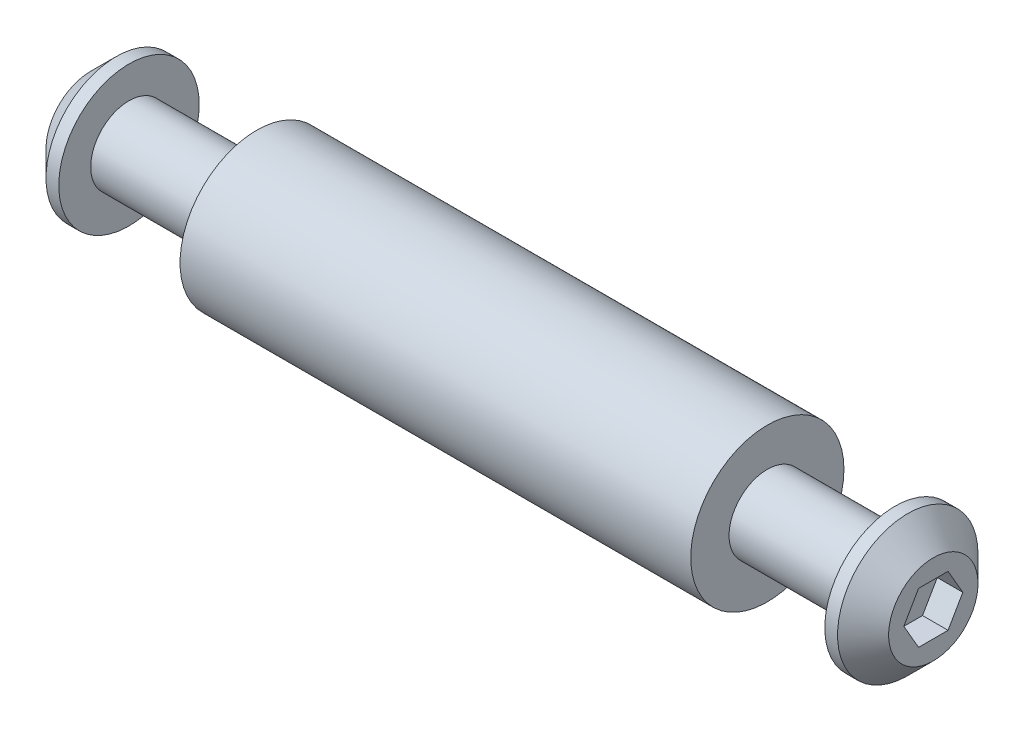
SolidWorks part; units mm, degrees
ref_plane "Front" through (0, 0, 0) normal (0, 0, 1) x (1, 0, 0)
ref_plane "Top" through (0, 0, 0) normal (0, 1, 0) x (1, 0, 0)
ref_plane "Right" through (0, 0, 0) normal (1, 0, 0) x (0, 0, -1)
sketch "Esquisse1" plane through (0, 0, 0) normal (0, 0, 1) x (1, 0, 0)
  line L0 (0, 0) -> (-18.7013, 0) construction
  line L1 (0, 0) -> (0, 7.2882) construction
  line L2 (10, 3) -> (-10, 3)
  line L3 (-10, 3) -> (-10, 1.5)
  line L4 (-10, 1.5) -> (-15, 1.5)
  line L5 (-15, 1.5) -> (-15, 2.75)
  line L6 (-15, 2.75) -> (-15.5, 2.75)
  line L7 (-15.5, 2.75) -> (-16.5, 1.75)
  line L8 (-16.5, 1.75) -> (-16.5, 0)
  line L9 (-16.5, 0) -> (16.5, 0)
  line L10 (10, 3) -> (10, 1.5)
  line L11 (10, 1.5) -> (15, 1.5)
  line L12 (15, 1.5) -> (15, 2.75)
  line L13 (15, 2.75) -> (15.5, 2.75)
  line L14 (15.5, 2.75) -> (16.5, 1.75)
  line L15 (16.5, 1.75) -> (16.5, 0)
  point P7 (-15.25, 2.75)
  point P13 (-15, 2.125)
  point P16 (0, 3)
  point P17 (15, 2.125)
  point P19 (15.25, 2.75)
  point P23 (-10.9122, 0)
  point P24 (-12.3736, 1.2641)
  point P25 (-11.9532, 2.4052)
  point P26 (-10.8321, 2.4853)
  point P27 (-13.7805, 1.5)
  point P28 (-13.2715, 2.6434)
  point P29 (-11.7221, 2.6886)
  point P30 (-16.3772, 2.761)
  point P31 (-17.3496, 1.8166)
  point P32 (-18.7013, 0)
  dimension "D1" = 3
  dimension "D2" = 6
  dimension "D3" = 20
  dimension "D4" = 5
  dimension "D5" = 1.5
  dimension "D6" = 0.5
  dimension "D7" = 45
  dimension "D8" = 5.5
revolve "Révolution1" add sketch "Esquisse1" angle 360 about L0
sketch "Esquisse2" plane through (16.5, 0, 0) normal (1, 0, 0) x (0, 0, -1)
  line L1 (0.5774, 1) -> (-0.5774, 1)
  line L2 (-0.5774, 1) -> (-1.1547, 0)
  line L3 (-1.1547, 0) -> (-0.5774, -1)
  line L4 (-0.5774, -1) -> (0.5774, -1)
  line L5 (0.5774, -1) -> (1.1547, 0)
  line L6 (1.1547, 0) -> (0.5774, 1)
  circle A0 centre (0, 0) radius 1 construction
  dimension "D1" = 2
extrude "Enlèv. mat.-Extru.1" cut sketch "Esquisse2" against normal blind 1
mirror "Symétrie1" about plane through (0, 0, 0) normal (1, 0, 0) of "Enlèv. mat.-Extru.1"
